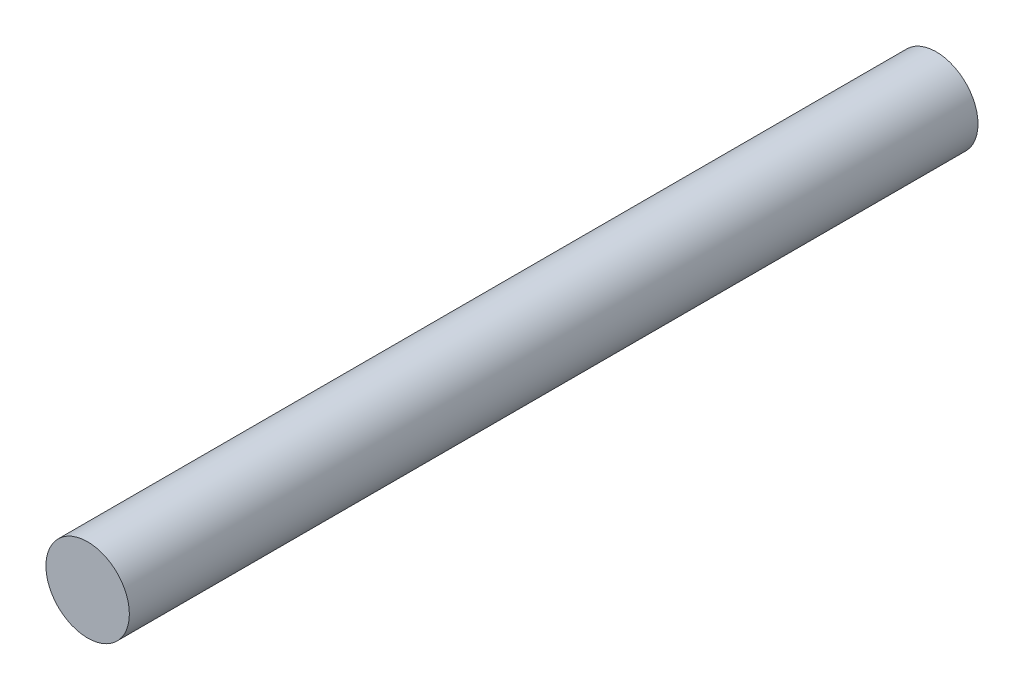
SolidWorks part; units mm, degrees
ref_plane "Front Plane" through (0, 0, 0) normal (0, 0, 1) x (1, 0, 0)
ref_plane "Top Plane" through (0, 0, 0) normal (0, 1, 0) x (1, 0, 0)
ref_plane "Right Plane" through (0, 0, 0) normal (1, 0, 0) x (0, 0, -1)
sketch "Sketch1" plane through (0, 0, 0) normal (0, 0, 1) x (1, 0, 0)
  circle A0 centre (0, 0) radius 4.7625
  dimension "D1" = 9.525
extrude "Boss-Extrude1" add sketch "Sketch1" along normal blind 96.8756
